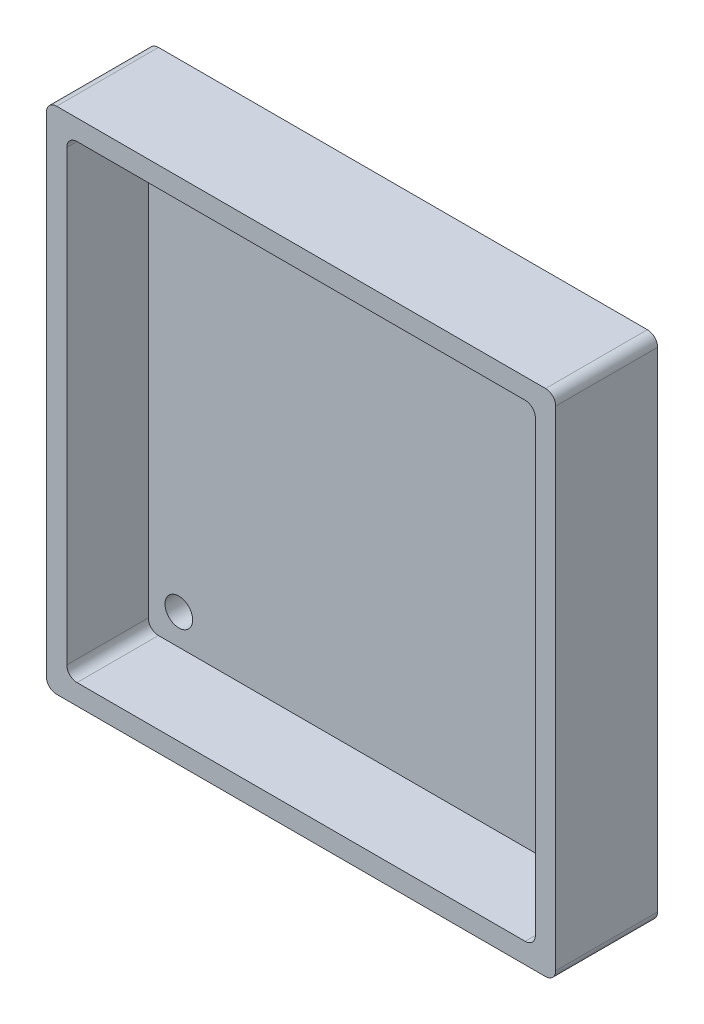
SolidWorks part; units mm, degrees
ref_plane "Front Plane" through (0, 0, 0) normal (0, 0, 1) x (1, 0, 0)
ref_plane "Top Plane" through (0, 0, 0) normal (0, 1, 0) x (1, 0, 0)
ref_plane "Right Plane" through (0, 0, 0) normal (1, 0, 0) x (0, 0, -1)
sketch "Sketch1" plane through (0, 0, 0) normal (0, 0, 1) x (1, 0, 0)
  line L1 (50, 50) -> (-50, 50)
  line L2 (50, 50) -> (50, -50)
  line L3 (50, -50) -> (-50, -50)
  line L4 (-50, 50) -> (-50, -50)
  line L5 (50, 50) -> (-50, -50) construction
  line L6 (50, -50) -> (-50, 50) construction
  point P0 (0, 0)
  dimension "D1" = 100
  dimension "D2" = 100
extrude "Boss-Extrude1" add sketch "Sketch1" along normal blind 20
ref_plane "Plane1" through (0, 0, 20) normal (0, 0, 1) x (1, 0, 0)
sketch "Sketch2" plane through (0, 0, 20) normal (0, 0, 1) x (1, 0, 0)
  line L1 (46, -46) -> (-46, -46)
  line L2 (46, -46) -> (46, 46)
  line L3 (46, 46) -> (-46, 46)
  line L4 (-46, -46) -> (-46, 46)
  line L5 (46, -46) -> (-46, 46) construction
  line L6 (46, 46) -> (-46, -46) construction
  point P0 (0, 0)
  dimension "D1" = 92
  dimension "D2" = 92
extrude "Cut-Extrude1" cut sketch "Sketch2" against normal blind 16
fillet "Fillet1" radius 2 8 edges at (-46, 46, 12) (46, 46, 12) (46, -46, 12) (-46, -46, 12) (50, -50, 10) (-50, -50, 10) (-50, 50, 10) (50, 50, 10)
sketch "Sketch3" plane through (0, 0, 0) normal (0, 0, 1) x (1, 0, 0)
  circle A1 centre (-40, 40) radius 2.714
  circle A2 centre (40, 40) radius 2.714
  circle A3 centre (40, -40) radius 2.714
  circle A4 centre (-40, -40) radius 2.714
  dimension "D4" = 4
extrude "Cut-Extrude2" cut sketch "Sketch3" along normal blind 16
